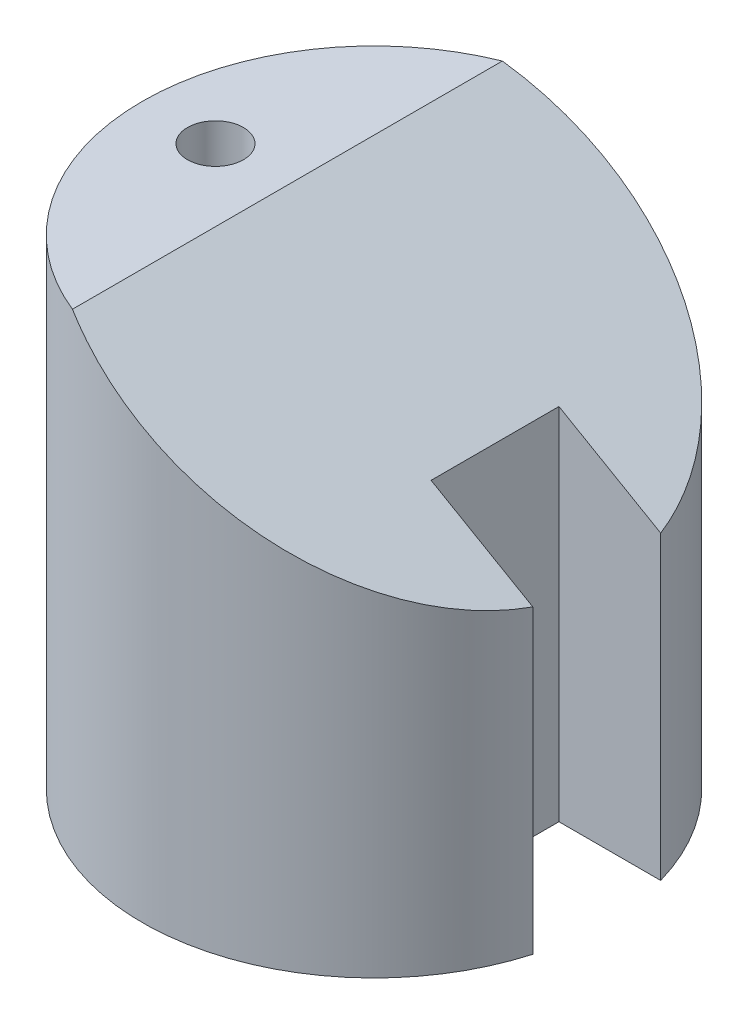
SolidWorks part; units mm, degrees
ref_plane "Front Plane" through (0, 0, 0) normal (0, 0, 1) x (1, 0, 0)
ref_plane "Top Plane" through (0, 0, 0) normal (0, 1, 0) x (1, 0, 0)
ref_plane "Right Plane" through (0, 0, 0) normal (1, 0, 0) x (0, 0, -1)
sketch "Sketch3" plane through (0, 0, 0) normal (0, 1, 0) x (1, 0, 0)
  circle A0 centre (0, 0) radius 29
  dimension "D1" = 58
extrude "Boss-Extrude1" add sketch "Sketch3" along normal blind 60
sketch "Sketch6" plane through (0, 0, 0) normal (0, 0, 1) x (1, 0, 0)
  line L0 (-10.8372, 60) -> (29, 37)
  line L1 (29, 60) -> (-29, 60) construction
  line L2 (29, 0) -> (29, 60) construction
  line L3 (29, 37) -> (29, 60)
  line L4 (29, 60) -> (-10.8372, 60)
  dimension "D1" = 30
  dimension "D2" = 46
extrude "Cut-Extrude1" cut sketch "Sketch6" against normal mid plane 60
sketch "Sketch8" plane through (0, 60, 0) normal (0, 1, 0) x (1, 0, 0)
  line L0 (-29, 0) -> (29, 0) construction
  line L1 (-10.8372, 26.899) -> (-10.8372, -26.899) construction
  arc A0 (-10.8372, -26.899) -> (-10.8372, 26.899) centre (0, 0) ccw construction
  circle A1 centre (-19.8372, 0) radius 3.5
  point P7 (0, 0)
  dimension "D1" = 9
extrude "Cut-Extrude2" cut sketch "Sketch8" against normal blind 20
sketch "Sketch15" plane through (23.2715, 40.3074, 0) normal (0.5, 0.866, 0) x (0.866, -0.5, 0)
  line L0 (0, 0) -> (6.6147, 0) construction
  line L1 (-9.3853, 8) -> (6.6147, 8)
  line L2 (-9.3853, 8) -> (-9.3853, -8)
  line L3 (-9.3853, -8) -> (6.6147, -8)
  line L4 (6.6147, 8) -> (6.6147, -8)
  ellipse E0 centre (-26.8716, 0) end of major axis (-60.3579, 0) minor radius 29 (-39.3853, -26.899) -> (-39.3853, 26.899) ccw construction
  point P6 (6.6147, 0)
  point P15 (6.6147, 0)
  dimension "D1" = 16
  dimension "D2" = 16
extrude "Cut-Extrude4" cut sketch "Sketch15" along direction (0, 1, 0) on the side against the normal blind 61 contours L2 L1 L4 L3
